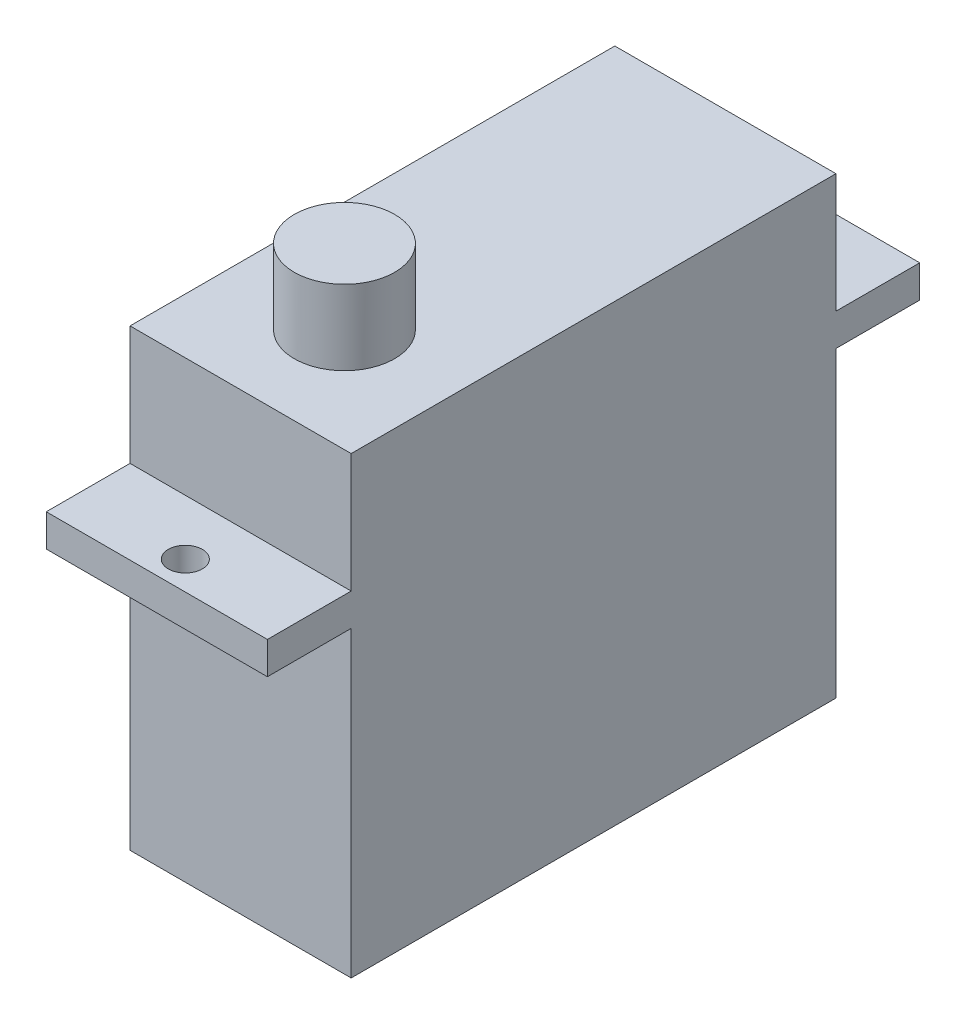
SolidWorks part; units mm, degrees
material "Servo"
ref_plane "前基準面" through (0, 0, 0) normal (0, 0, 1) x (1, 0, 0)
ref_plane "上基準面" through (0, 0, 0) normal (0, 1, 0) x (1, 0, 0)
ref_plane "右基準面" through (0, 0, 0) normal (1, 0, 0) x (0, 0, -1)
sketch "草圖1" plane through (0, 0, 0) normal (1, 0, 0) x (0, 0, -1)
  line L0 (14.25, 10.8) -> (19.175, 10.8)
  line L2 (-14.25, 8.9) -> (-14.25, -8.9)
  line L3 (-14.25, -8.9) -> (14.25, -8.9)
  line L4 (14.25, 8.9) -> (14.25, -8.9)
  line L5 (-14.25, 8.9) -> (14.25, -8.9) construction
  line L6 (-14.25, -8.9) -> (14.25, 8.9) construction
  line L7 (-19.175, 10.8) -> (-14.25, 10.8)
  line L8 (-19.175, 10.8) -> (-19.175, 8.9)
  line L9 (-19.175, 8.9) -> (-14.25, 8.9)
  line L10 (19.175, 10.8) -> (19.175, 8.9)
  line L11 (-19.175, 10.8) -> (19.175, 8.9) construction
  line L12 (-19.175, 8.9) -> (19.175, 10.8) construction
  line L13 (-14.25, 17.8) -> (14.25, 17.8)
  line L14 (-14.25, 17.8) -> (-14.25, 10.8)
  line L16 (14.25, 17.8) -> (14.25, 10.8)
  line L17 (-14.25, 17.8) -> (14.25, 10.8) construction
  line L18 (-14.25, 10.8) -> (14.25, 17.8) construction
  line L19 (14.25, 8.9) -> (19.175, 8.9)
  line L20 (0, 14.3) -> (0, 0) construction
  point P0 (0, 0)
  point P6 (0, 9.85)
  point P11 (0, 14.3)
  dimension "D1" = 28.5
  dimension "D2" = 19.7
  dimension "D3" = 26.7
  dimension "D4" = 17.8
  dimension "D5" = 38.35
extrude "填料-伸長1" add sketch "草圖1" along normal blind 13
sketch "草圖2" plane through (0, 17.8, 0) normal (0, 1, 0) x (1, 0, 0)
  line L1 (13, -14.25) -> (0, -14.25) construction
  line L3 (0, 14.25) -> (0, -14.25) construction
  line L4 (13, 14.25) -> (13, -14.25) construction
  line L5 (6.5, -14.25) -> (6.5, 14.25) construction
  line L6 (13, 14.25) -> (0, 14.25) construction
  arc A0 (3.5088, -1.9792) -> (9.4912, -1.9792) centre (6.5, -7.75) ccw
  arc A1 (9.4912, -1.9792) -> (3.5088, -1.9792) centre (6.5, -1.75) ccw
  dimension "D1" = 6
  dimension "D2" = 6
sketch "草圖4" plane through (0, 10.8, 0) normal (0, 1, 0) x (1, 0, 0)
  line L0 (6.5, -19.175) -> (6.5, 19.175) construction
  line L1 (13, -19.175) -> (0, -19.175) construction
  line L2 (13, 19.175) -> (0, 19.175) construction
  line L3 (6.5, 17.5) -> (6.5, -17.5) construction
  circle A0 centre (6.5, 17.5) radius 1
  circle A1 centre (6.5, -17.5) radius 1
  point P12 (6.5, 0)
  point P13 (6.5, 0)
  dimension "D3" = 2
  dimension "D1" = 35
extrude "除料-伸長1" cut sketch "草圖4" against normal through all
sketch "草圖6" plane through (0, 17.8, 0) normal (0, 1, 0) x (1, 0, 0)
  line L0 (6.5, -14.25) -> (6.5, 14.25) construction
  line L1 (13, -14.25) -> (0, -14.25) construction
  circle A0 centre (6.5, -8.145) radius 2.95
  circle A4 centre (6.5, -17.5) radius 1 construction
  dimension "D2" = 5.9
  dimension "D3" = 9.355
  dimension "D1" = 6.105
extrude "填料-伸長2" add sketch "草圖6" along normal blind 4.4
